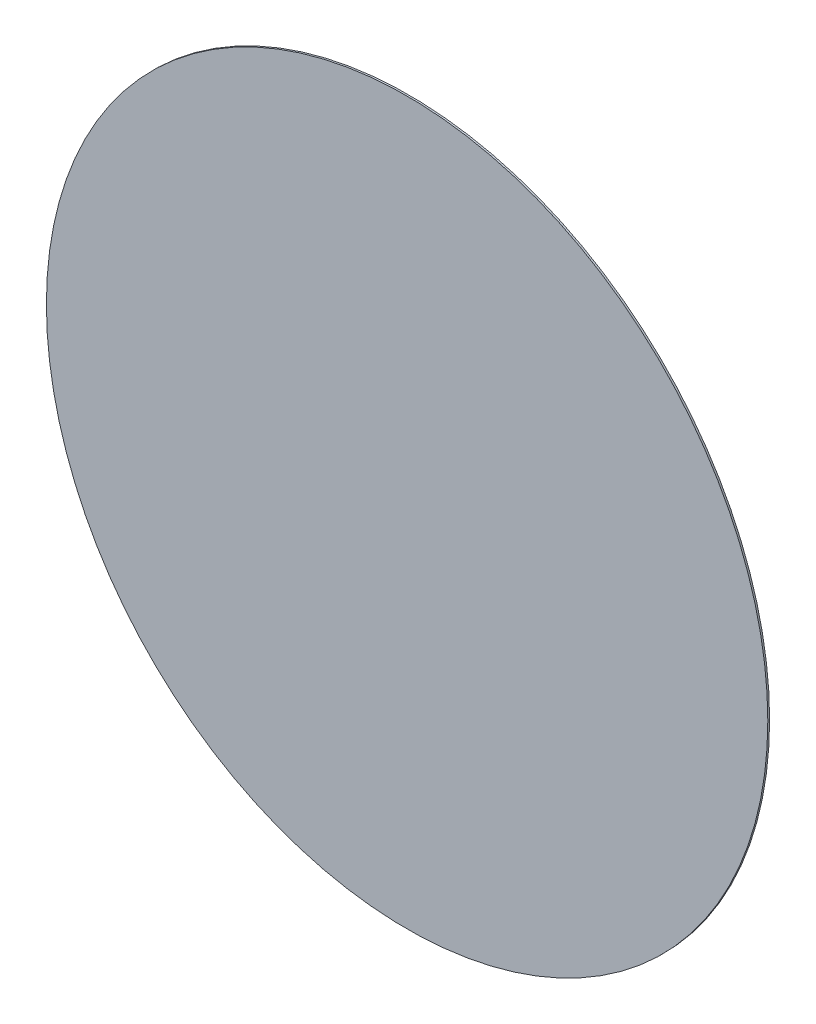
SolidWorks part; units mm, degrees
ref_plane "前视基准面" through (0, 0, 0) normal (0, 0, 1) x (1, 0, 0)
ref_plane "上视基准面" through (0, 0, 0) normal (0, 1, 0) x (1, 0, 0)
ref_plane "右视基准面" through (0, 0, 0) normal (1, 0, 0) x (0, 0, -1)
sketch "草图1" plane through (0, 0, 0) normal (0, 0, 1) x (1, 0, 0)
  circle A0 centre (0, 0) radius 200
extrude "凸台-拉伸1" add sketch "草图1" along normal blind 1
